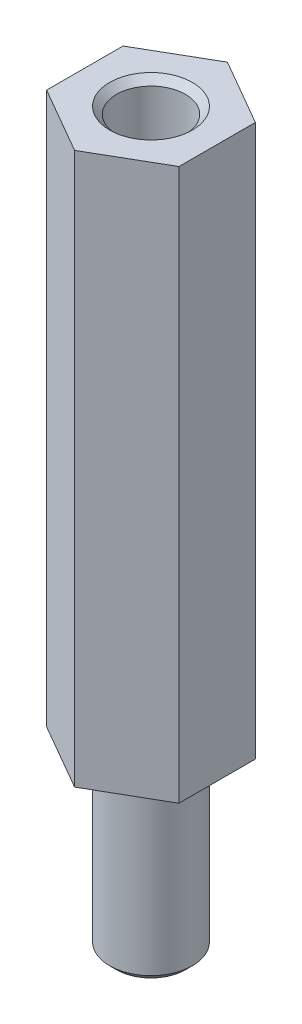
SolidWorks part; units mm, degrees
ref_plane "Front Plane" through (0, 0, 0) normal (0, 0, 1) x (1, 0, 0)
ref_plane "Top Plane" through (0, 0, 0) normal (0, 1, 0) x (1, 0, 0)
ref_plane "Right Plane" through (0, 0, 0) normal (1, 0, 0) x (0, 0, -1)
sketch "Profile" plane through (0, 0, 0) normal (0, 1, 0) x (1, 0, 0)
  line L1 (-2.4, -1.3856) -> (0, -2.7713)
  line L2 (0, -2.7713) -> (2.4, -1.3856)
  line L3 (2.4, -1.3856) -> (2.4, 1.3856)
  line L4 (2.4, 1.3856) -> (0, 2.7713)
  line L5 (0, 2.7713) -> (-2.4, 1.3856)
  line L6 (-2.4, 1.3856) -> (-2.4, -1.3856)
  circle A0 centre (0, 0) radius 2.4 construction
  dimension "SIZE-A/F-HEX" = 4.8
extrude "SPACER" add sketch "Profile" along normal blind 20
sketch "HOLE" plane through (0, 20, 0) normal (0, 1, 0) x (1, 0, 0)
  circle A0 centre (0, 0) radius 1.25
  dimension "MINOR DIA" = 2.5
extrude "BLIND_HOLE" cut sketch "HOLE" against normal blind 6.5
cosmetic thread "HOLE_TAP"
chamfer "HOLE_Chamfer" distance 0.25 angle 45 1 edges at (0, 20, 1.25)
sketch "Sketch6" plane through (0, 0, 0) normal (0, 0, 1) x (1, 0, 0)
  line L7 (1.25, 13.5) -> (-1.25, 13.5) construction
  line L8 (1.25, 13.5) -> (-1.25, 13.5) construction
  line L9 (0, 13.5) -> (-1.25, 13.5)
  line L10 (0, 12.7489) -> (-1.25, 13.5)
  line L11 (0, 12.7489) -> (0, 13.5)
  point P9 (0, 13.5)
  dimension "D2" = 31
revolve "DRILL_CUT" cut sketch "Sketch6" angle 360 mid plane about L11
sketch "SHAFT" plane through (0, 0, 0) normal (0, -1, 0) x (1, 0, 0)
  circle A0 centre (0, 0) radius 1.5
  dimension "MAIL_NOMINAL DIA" = 3
extrude "MAIL_SHAFT" add sketch "SHAFT" along normal blind 6.5
cosmetic thread "SHAFT_TAP"
chamfer "SHAFT_Chamfer" distance 0.25 angle 45 1 edges at (0, -6.5, -1.5)
ref_plane "Plane1" through (0, 0, -2.7713) normal (0, -1, 0) x (-1, 0, 0)
